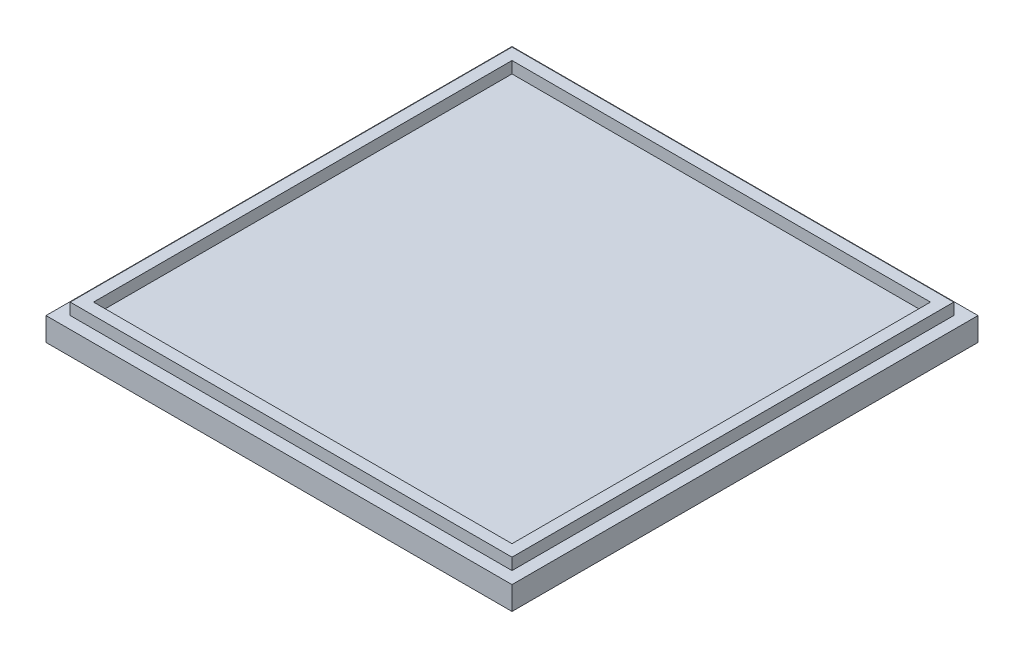
SolidWorks part; units mm, degrees
ref_plane "Front Plane" through (0, 0, 0) normal (0, 0, 1) x (1, 0, 0)
ref_plane "Top Plane" through (0, 0, 0) normal (0, 1, 0) x (1, 0, 0)
ref_plane "Right Plane" through (0, 0, 0) normal (1, 0, 0) x (0, 0, -1)
sketch "Croquis1" plane through (0, 0, 0) normal (0, 1, 0) x (1, 0, 0)
  line L1 (-100, -100) -> (100, -100)
  line L2 (-100, -100) -> (-100, 100)
  line L3 (-100, 100) -> (100, 100)
  line L4 (100, -100) -> (100, 100)
  line L5 (-100, -100) -> (100, 100) construction
  line L6 (-100, 100) -> (100, -100) construction
  point P0 (0, 0)
  dimension "D1" = 200
  dimension "D2" = 200
extrude "Saliente-Extruir1" add sketch "Croquis1" along normal blind 10
sketch "Croquis2" plane through (0, 10, 0) normal (0, 1, 0) x (1, 0, 0)
  line L10 (-89.8, 89.8) -> (-89.8, -89.8)
  line L11 (-89.8, -89.8) -> (89.8, -89.8)
  line L12 (89.8, -89.8) -> (89.8, 89.8)
  line L13 (89.8, 89.8) -> (-89.8, 89.8)
  line L14 (-94.8, -94.8) -> (94.8, -94.8)
  line L15 (94.8, -94.8) -> (94.8, 94.8)
  line L16 (94.8, 94.8) -> (-94.8, 94.8)
  line L17 (-94.8, 94.8) -> (-94.8, -94.8)
  line L18 (-94.8, -94.8) -> (94.8, -94.8)
  line L19 (94.8, -94.8) -> (94.8, 94.8)
  line L20 (94.8, 94.8) -> (-94.8, 94.8)
  line L21 (-94.8, 94.8) -> (-94.8, -94.8)
  dimension "D1" = 5.2
  dimension "D2" = 5
extrude "Saliente-Extruir2" add sketch "Croquis2" along normal blind 5
